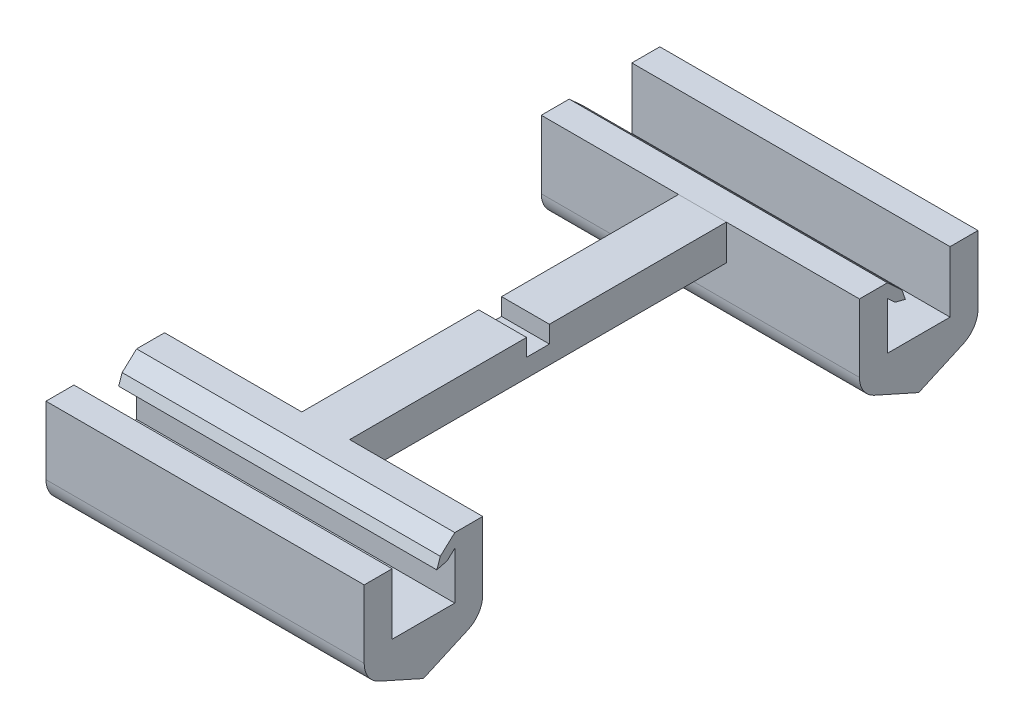
SolidWorks part; units mm, degrees
ref_plane "Front Plane" through (0, 0, 0) normal (0, 0, 1) x (1, 0, 0)
ref_plane "Top Plane" through (0, 0, 0) normal (0, 1, 0) x (1, 0, 0)
ref_plane "Right Plane" through (0, 0, 0) normal (1, 0, 0) x (0, 0, -1)
sketch "Sketch1" plane through (0, 0, 0) normal (1, 0, 0) x (0, 0, -1)
  line L0 (0, 0) -> (0, 50000) construction
  line L1 (8.6339, -0.7753) -> (8.6339, -0.2318) construction
  line L2 (9.351, -1.1632) -> (9.0754, -0.9097) construction
  line L3 (9.2108, -0.7625) -> (8.94, -1.0569) construction
  line L4 (8.94, -1.0569) -> (8.6339, -0.7753)
  line L5 (9.351, -1.1632) -> (8.94, -1.0569)
  line L6 (9.2108, -0.7625) -> (9.351, -1.1632)
  line L7 (8.6339, -0.2318) -> (9.2108, -0.7625)
  line L8 (7.5181, -0.2318) -> (7.5181, -2.9453)
  line L9 (8.1094, -3.858) -> (9.8839, -4.6525)
  line L10 (11.1339, -0.2318) -> (12.2498, -0.2318)
  line L11 (11.1339, -2.6693) -> (11.1339, -0.2318)
  line L12 (-8.6339, -0.2318) -> (-7.5181, -0.2318)
  line L13 (-8.6339, -2.6693) -> (-8.6339, -0.7753)
  line L14 (-11.1339, -2.6693) -> (-8.6339, -2.6693)
  line L15 (-11.6584, -3.858) -> (-9.8839, -4.6525)
  line L16 (-12.2498, -0.2318) -> (-12.2498, -2.9453)
  line L17 (-11.1339, -2.6693) -> (-11.1339, -0.2318)
  line L18 (-11.1339, -0.2318) -> (-12.2498, -0.2318)
  line L19 (-8.1094, -3.858) -> (-9.8839, -4.6525)
  line L20 (-7.5181, -0.2318) -> (-7.5181, -2.9453)
  line L21 (-8.6339, -0.2318) -> (-9.2108, -0.7625)
  line L22 (-9.2108, -0.7625) -> (-9.351, -1.1632)
  line L23 (-9.351, -1.1632) -> (-8.94, -1.0569)
  line L24 (-8.94, -1.0569) -> (-8.6339, -0.7753)
  line L25 (-9.2108, -0.7625) -> (-8.94, -1.0569) construction
  line L26 (-9.351, -1.1632) -> (-9.0754, -0.9097) construction
  line L27 (-8.6339, -0.7753) -> (-8.6339, -0.2318) construction
  line L28 (12.2498, -0.2318) -> (12.2498, -2.9453)
  line L29 (11.6584, -3.858) -> (9.8839, -4.6525)
  line L30 (11.1339, -2.6693) -> (8.6339, -2.6693)
  line L31 (8.6339, -2.6693) -> (8.6339, -0.7753)
  line L32 (8.6339, -0.2318) -> (7.5181, -0.2318)
  arc A0 (-8.1094, -3.858) -> (-7.5181, -2.9453) centre (-8.5181, -2.9453) ccw
  arc A1 (-11.6584, -3.858) -> (-12.2498, -2.9453) centre (-11.2498, -2.9453) cw
  arc A2 (11.6584, -3.858) -> (12.2498, -2.9453) centre (11.2498, -2.9453) ccw
  arc A3 (8.1094, -3.858) -> (7.5181, -2.9453) centre (8.5181, -2.9453) cw
  point P3 (0, 0)
  point P27 (-7.5181, -3.5932)
  point P35 (0, 0)
  point P42 (7.5181, -3.5932)
  point P46 (0, 0)
  point P47 (0, 0)
  dimension "D3" = 1
  dimension "D2" = 1.1159
  dimension "D4" = 0.4
  dimension "D5" = 2.7135
  dimension "D6" = 1.9442
  dimension "D7" = 1.9442
  dimension "D8" = 2.7135
  dimension "D9" = 1.1159
extrude "Boss-Extrude1" add sketch "Sketch1" along normal blind 12.7
sketch "Sketch2" plane through (0, 0, -7.5181) normal (0, 0, 1) x (1, 0, 0)
  line L1 (5.4781, -0.2318) -> (7.3878, -0.2318)
  line L2 (5.4781, -0.2318) -> (5.4781, -1.6416)
  line L3 (5.4781, -1.6416) -> (7.3878, -1.6416) construction
  line L4 (7.3878, -0.2318) -> (7.3878, -1.6416)
  line L5 (5.4781, -1.6416) -> (6.433, -2.5964)
  line L6 (6.433, -2.5964) -> (7.3878, -1.6416)
  line L8 (12.7, -0.2318) -> (0, -0.2318) construction
extrude "Boss-Extrude2" add sketch "Sketch2" along normal up to next
sketch "Sketch3" plane through (5.4781, 0, 0) normal (-1, 0, 0) x (0, 0, 1)
  line L0 (0, 0) -> (0, -50000) construction
  line L1 (7.5181, -0.2318) -> (-7.5181, -0.2318) construction
  line L2 (0.456, -0.9172) -> (0.456, -0.2318)
  line L3 (-0.456, -0.9172) -> (-0.456, -0.2318)
  line L4 (-0.456, -0.2318) -> (0.456, -0.2318)
  line L5 (0.456, -0.9172) -> (-0.456, -0.9172)
  point P4 (0, -0.2318)
  dimension "D1" = 0.912
extrude "Cut-Extrude1" cut sketch "Sketch3" against normal up to next (1.9097 mm away)
